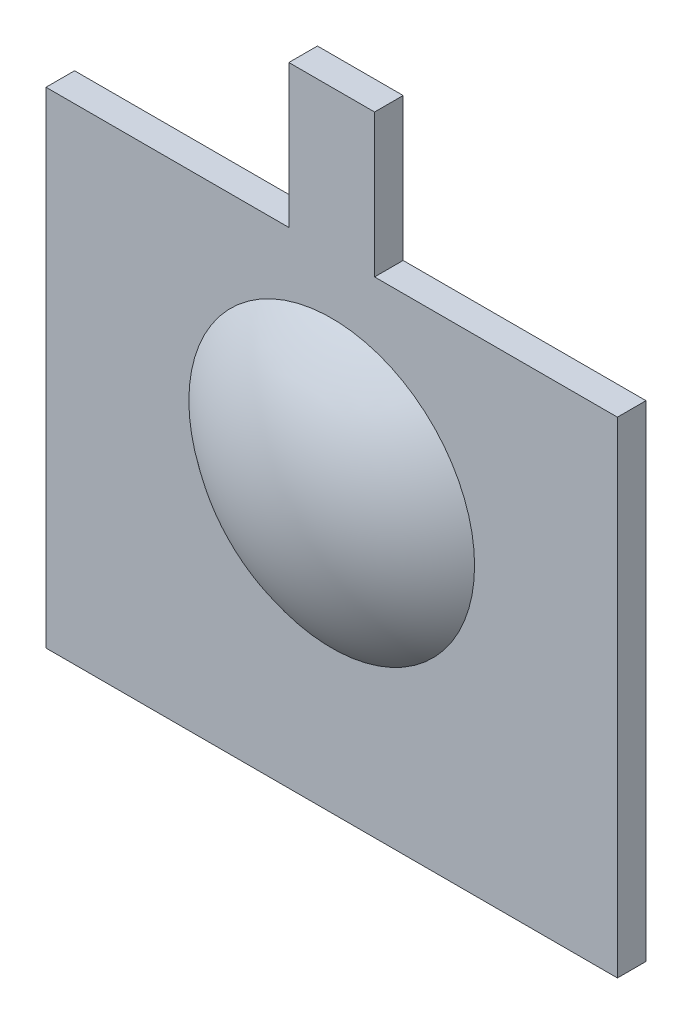
SolidWorks part; units mm, degrees
ref_plane "Front Plane" through (0, 0, 0) normal (0, 0, 1) x (1, 0, 0)
ref_plane "Top Plane" through (0, 0, 0) normal (0, 1, 0) x (1, 0, 0)
ref_plane "Right Plane" through (0, 0, 0) normal (1, 0, 0) x (0, 0, -1)
ref_plane "Plate Base y1.95" through (0, 1.95, 0) normal (0, 1, 0) x (1, 0, 0)
sketch "Plus Plate 10 x 8.5 x 0.5 Sketch" plane through (0, 1.95, 0) normal (0, 1, 0) x (1, 0, 0)
  line L0 (9.3, 64.85) -> (19.3, 64.85)
  line L1 (19.3, 64.85) -> (19.3, 65.35)
  line L2 (19.3, 65.35) -> (9.3, 65.35)
  line L3 (9.3, 65.35) -> (9.3, 64.85)
extrude "Plus Plate 10 x 8.5 x 0.5" add sketch "Plus Plate 10 x 8.5 x 0.5 Sketch" along normal blind 8.5
ref_plane "Plate Top y10.45" through (0, 10.45, 0) normal (0, 1, 0) x (1, 0, 0)
sketch "Solder Tab 1.5 x 2.5 Sketch" plane through (0, 10.45, 0) normal (0, 1, 0) x (1, 0, 0)
  line L0 (13.55, 64.85) -> (15.05, 64.85)
  line L1 (15.05, 64.85) -> (15.05, 65.35)
  line L2 (15.05, 65.35) -> (13.55, 65.35)
  line L3 (13.55, 65.35) -> (13.55, 64.85)
extrude "Solder Tab 1.5 x 2.5" add sketch "Solder Tab 1.5 x 2.5 Sketch" along normal blind 2.5
ref_plane "Contact Axis Plane y6.95" through (0, 6.95, 0) normal (0, 1, 0) x (1, 0, 0)
sketch "Dimple 0.9 Sketch" plane through (0, 6.95, 0) normal (0, 1, 0) x (1, 0, 0)
  line L0 (14.3, 65.85) -> (14.3, 62.95) construction
  line L1 (14.3, 64.85) -> (16.8, 64.85)
  line L2 (14.3, 63.95) -> (14.3, 64.85)
  arc A0 (16.8, 64.85) -> (14.3, 63.95) centre (14.3, 67.8722) cw
revolve "Dimple 0.9" add sketch "Dimple 0.9 Sketch" angle 360 about L0
